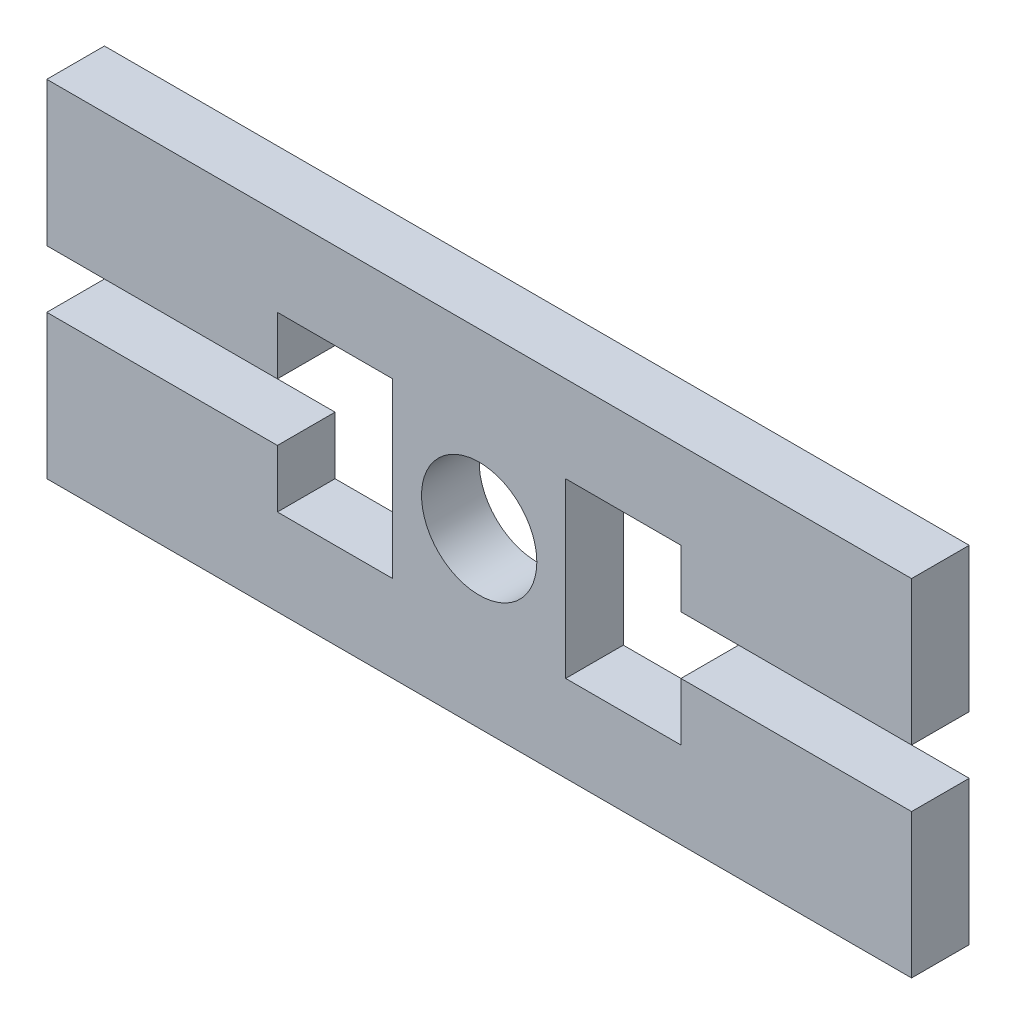
SolidWorks part; units mm, degrees
ref_plane "Front Plane" through (0, 0, 0) normal (0, 0, 1) x (1, 0, 0)
ref_plane "Top Plane" through (0, 0, 0) normal (0, 1, 0) x (1, 0, 0)
ref_plane "Right Plane" through (0, 0, 0) normal (1, 0, 0) x (0, 0, -1)
sketch "Sketch1" plane through (0, 0, 0) normal (0, 0, 1) x (1, 0, 0)
  line L0 (-44.45, 0) -> (-44.45, -6.35) construction
  line L1 (-95.25, 38.1) -> (95.25, 38.1)
  line L2 (-95.25, 38.1) -> (-95.25, 6.35)
  line L3 (-95.25, -38.1) -> (95.25, -38.1)
  line L4 (95.25, 38.1) -> (95.25, 6.35)
  line L5 (-95.25, 38.1) -> (95.25, -38.1) construction
  line L6 (-95.25, -38.1) -> (95.25, 38.1) construction
  line L7 (-19.05, 0) -> (0, 0) construction
  line L8 (-19.05, 0) -> (-19.05, 11.5629) construction
  line L9 (-19.05, 11.5629) -> (-19.05, 19.05) construction
  line L10 (-19.05, 19.05) -> (-44.45, 19.05) construction
  line L11 (-44.45, 19.05) -> (-44.45, 6.35) construction
  line L12 (-44.45, 6.35) -> (-44.45, 0) construction
  line L13 (-44.45, 6.35) -> (-95.25, 6.35) construction
  line L14 (0, 38.1) -> (0, 0) construction
  line L15 (0, 0) -> (0, -38.1) construction
  line L16 (-95.25, 6.35) -> (-44.45, 6.35)
  line L17 (-44.45, 6.35) -> (-44.45, 19.05)
  line L18 (-44.45, 19.05) -> (-19.05, 19.05)
  line L19 (-19.05, 19.05) -> (-19.05, -19.05)
  line L20 (19.05, 19.05) -> (19.05, -19.05)
  line L21 (44.45, 19.05) -> (19.05, 19.05)
  line L22 (44.45, 6.35) -> (44.45, 19.05)
  line L23 (95.25, 6.35) -> (44.45, 6.35)
  line L24 (95.25, -6.35) -> (44.45, -6.35)
  line L25 (44.45, -6.35) -> (44.45, -19.05)
  line L26 (44.45, -19.05) -> (19.05, -19.05)
  line L27 (-44.45, -19.05) -> (-19.05, -19.05)
  line L28 (-44.45, -6.35) -> (-44.45, -19.05)
  line L29 (-95.25, -6.35) -> (-44.45, -6.35)
  line L30 (-19.05, 0) -> (-44.45, 0) construction
  line L31 (0, 0) -> (19.05, 0) construction
  line L32 (-95.25, -6.35) -> (-95.25, -38.1)
  line L33 (95.25, -6.35) -> (95.25, -38.1)
  circle A0 centre (0, 0) radius 12.7
  point P0 (0, 0)
  point P28 (19.05, 0)
  dimension "D5" = 25.4
  dimension "D1" = 6.35
  dimension "D2" = 12.7
  dimension "D3" = 25.4
  dimension "D4" = 50.8
  dimension "D6" = 19.05
  dimension "D7" = 76.2
extrude "Boss-Extrude1" add sketch "Sketch1" along normal blind 12.7
